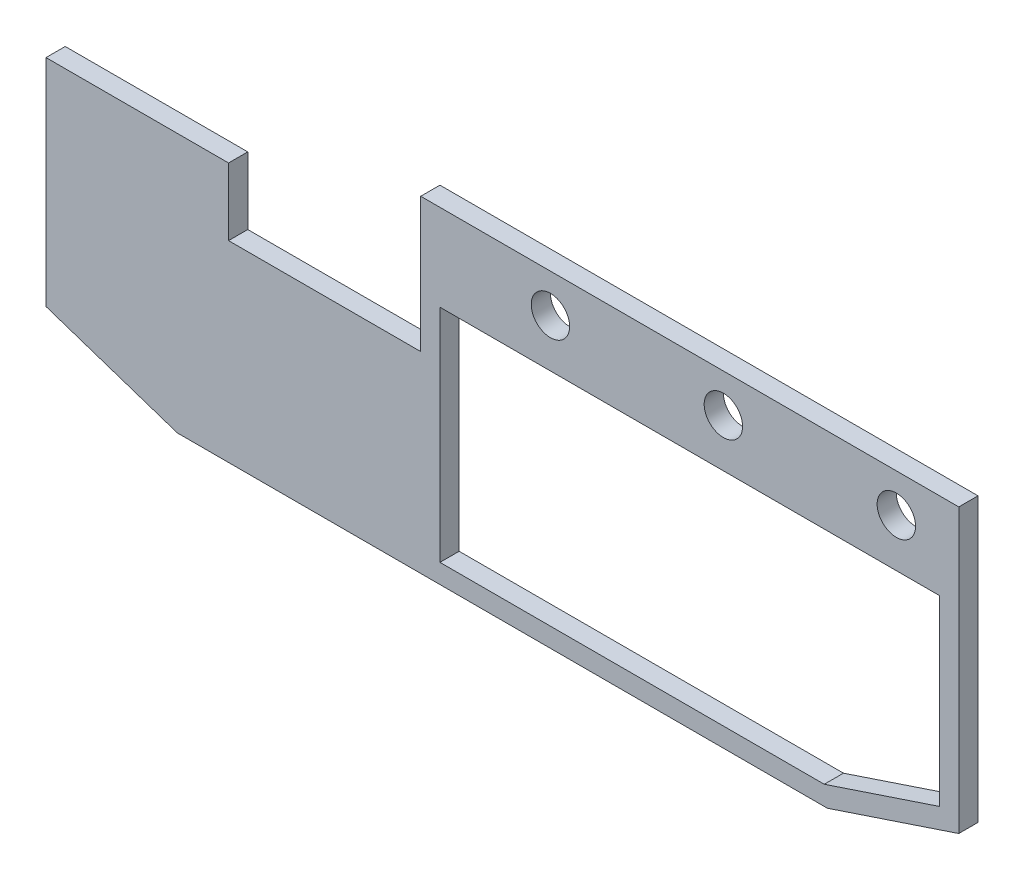
SolidWorks part; units mm, degrees
ref_plane "Front Plane" through (0, 0, 0) normal (0, 0, 1) x (1, 0, 0)
ref_plane "Top Plane" through (0, 0, 0) normal (0, 1, 0) x (1, 0, 0)
ref_plane "Right Plane" through (0, 0, 0) normal (1, 0, 0) x (0, 0, -1)
sketch "Sketch1" plane through (0, 0, 0) normal (0, 0, 1) x (1, 0, 0)
  line L0 (0, 0) -> (0, -19)
  line L5 (0, -19) -> (-12, -23)
  line L6 (-12, -23) -> (-79, -23)
  line L7 (-79, -23) -> (-91, -19)
  line L8 (-91, -19) -> (-91, 0)
  line L9 (-91, 0) -> (-76, 0)
  line L10 (-76, 0) -> (-76, -7)
  line L11 (-76, -7) -> (-52, -7)
  line L12 (-52, -7) -> (-52, 0)
  line L13 (-52, 0) -> (0, 0)
  point P0 (0, 0)
  dimension "D1" = 91
  dimension "D2" = 23
  dimension "D3" = 12
  dimension "D4" = 4
  dimension "D5" = 7
  dimension "D6" = 15
  dimension "D7" = 52
sketch "Sketch2" plane through (0, 0, 0) normal (0, 0, 1) x (1, 0, 0)
  line L0 (2, 9) -> (-54, 9)
  line L1 (-54, 9) -> (-54, -5)
  line L2 (-54, -5) -> (-74, -5)
  line L3 (-74, -5) -> (-74, 2)
  line L4 (-74, 2) -> (-93, 2)
  line L5 (-93, 2) -> (-93, -20.4415)
  line L6 (-93, -20.4415) -> (-79.3246, -25)
  line L7 (-79.3246, -25) -> (-11.6754, -25)
  line L8 (-11.6754, -25) -> (2, -20.4415)
  line L9 (2, -20.4415) -> (2, 9)
  line L10 (0, 0) -> (0, -19) construction
  line L12 (-52, -7) -> (-52, 0) construction
  line L13 (-76, -7) -> (-52, -7) construction
  line L14 (-76, 0) -> (-76, -7) construction
  line L15 (-91, 0) -> (-76, 0) construction
  line L16 (-91, -19) -> (-91, 0) construction
  line L17 (-12, -23) -> (-79, -23) construction
  line L18 (0, -19) -> (-12, -23) construction
  line L19 (-79, -23) -> (-91, -19) construction
  line L21 (-52, 0) -> (0, 0) construction
  dimension "D1" = 2
  dimension "D2" = 2
  dimension "D3" = 2
  dimension "D4" = 2
  dimension "D5" = 2
  dimension "D6" = 2
  dimension "D7" = 2
  dimension "D8" = 2
  dimension "D9" = 2
  dimension "D10" = 9
extrude "Boss-Extrude1" add sketch "Sketch2" against normal blind 2
hole_wizard "Ø4.0mm Dowel Hole1" positions "Sketch3" profile "Sketch4" hole size "Ø4.0" standard "ANSI Metric" end condition up to next
sketch "Sketch3" plane through (0, 0, 0) normal (0, 0, 1) x (1, 0, 0)
  line L0 (-52, 0) -> (0, 0) construction
  line L1 (0, 0) -> (0, -19) construction
  point P0 (-40.5, 5)
  point P2 (-22.5, 5)
  point P4 (-4.5, 5)
  dimension "D1" = 5
  dimension "D2" = 4.5
  dimension "D3" = 18
  dimension "D4" = 18
sketch "Sketch4" plane through (-40.5, 5, 0) normal (1, 0, 0) x (0, -1, 0)
  line L0 (0, 0) -> (0, 2)
  line L1 (0, 2) -> (2, 2)
  line L2 (2, 2) -> (2, 0)
  line L5 (2, 0) -> (0, 0)
  line L11 (0, -6.35) -> (0, 107.95) construction
  dimension "Thru Hole Dia." = 4
  dimension "Thru Hole Depth" = 2
extrude "Cut-Extrude1" cut sketch "Sketch1" against normal up to next
sketch "Sketch5" plane through (0, 0, 0) normal (0, 0, 1) x (1, 0, 0)
  line L0 (-52, -7) -> (-52, -23)
  line L1 (-79, -23) -> (-12, -23) construction
  line L2 (-52, -23) -> (-79, -23)
  line L3 (-79, -23) -> (-91, -19)
  line L4 (-91, -19) -> (-91, 0)
  line L5 (-91, 0) -> (-76, 0)
  line L6 (-76, 0) -> (-76, -7)
  line L7 (-76, -7) -> (-52, -7)
extrude "Boss-Extrude2" add sketch "Sketch5" against normal up to surface (2 mm away) up to face at (-52.9, -9.8, -2)
equation "\"WALLTHICK\"= 2mm"
equation "\"D1@Sketch2\"=\"WALLTHICK\""
equation "\"D2@Sketch2\"=\"WALLTHICK\""
equation "\"D3@Sketch2\"=\"WALLTHICK\""
equation "\"D4@Sketch2\"=\"WALLTHICK\""
equation "\"D5@Sketch2\"=\"WALLTHICK\""
equation "\"D6@Sketch2\"=\"WALLTHICK\""
equation "\"D7@Sketch2\"=\"WALLTHICK\""
equation "\"D8@Sketch2\"=\"WALLTHICK\""
equation "\"D9@Sketch2\"=\"WALLTHICK\""
equation "\"HOLEDIST\"= 5mm"
equation "\"D10@Sketch2\"=\"HOLEDIST\" + 4mm"
equation "\"D1@Sketch3\"=\"HOLEDIST\""
